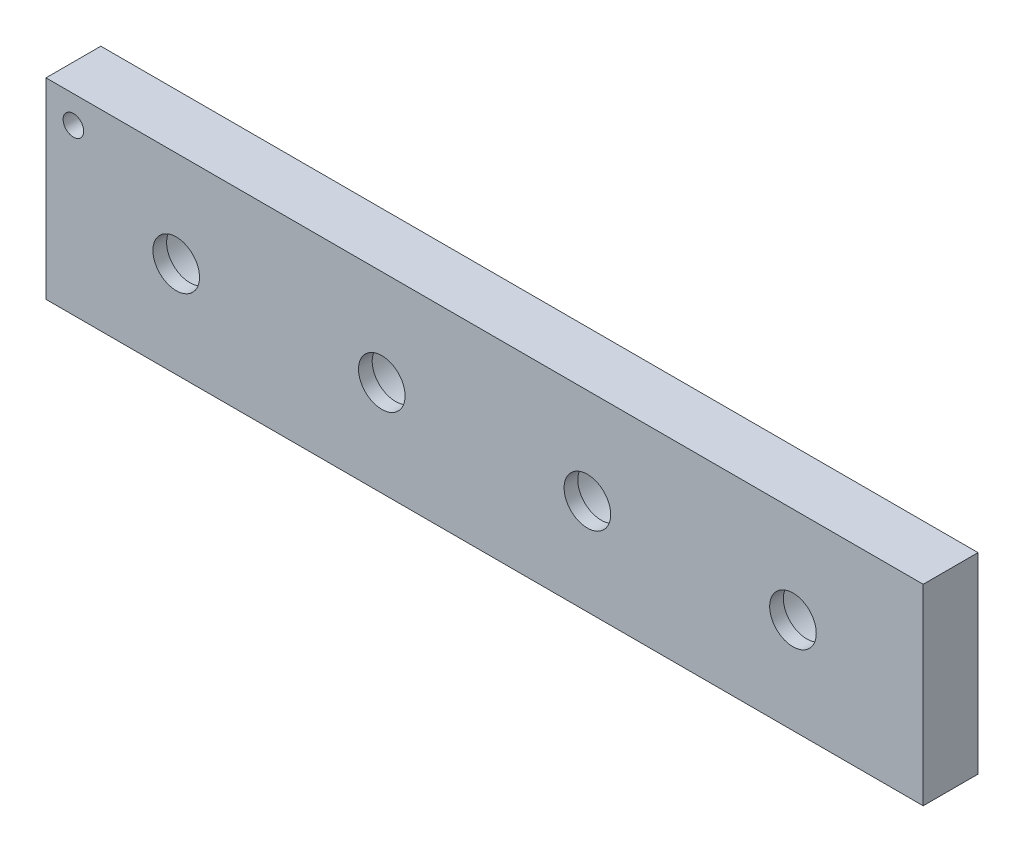
SolidWorks part; units mm, degrees
ref_plane "Front Plane" through (0, 0, 0) normal (0, 0, 1) x (1, 0, 0)
ref_plane "Top Plane" through (0, 0, 0) normal (0, 1, 0) x (1, 0, 0)
ref_plane "Right Plane" through (0, 0, 0) normal (1, 0, 0) x (0, 0, -1)
sketch "Coupon_bar_64x14x4_profile" plane through (0, 0, 0) normal (0, 0, 1) x (1, 0, 0)
  line L1 (-32, -7) -> (32, -7)
  line L2 (-32, -7) -> (-32, 7)
  line L3 (-32, 7) -> (32, 7)
  line L4 (32, -7) -> (32, 7)
  dimension "D1" = 64
  dimension "D2" = 14
extrude "Coupon_bar_64x14x4" add sketch "Coupon_bar_64x14x4_profile" along normal blind 4
sketch "Press_sockets_5p70_5p80_5p90_6p00_depth3_profile" plane through (0, 0, 0) normal (0, 0, 1) x (1, 0, 0)
  circle A0 centre (-22.5, 0) radius 2.85
  circle A1 centre (-7.5, 0) radius 2.9
  circle A2 centre (7.5, 0) radius 2.95
  circle A3 centre (22.5, 0) radius 3
  dimension "D1" = 5.7
  dimension "D2" = 5.8
  dimension "D3" = 5.9
  dimension "D4" = 6
extrude "Press_sockets_5p70_5p80_5p90_6p00_depth3" cut sketch "Press_sockets_5p70_5p80_5p90_6p00_depth3_profile" along normal blind 3
sketch "M3_centre_screw_clearance_profile" plane through (0, 0, 0) normal (0, 0, 1) x (1, 0, 0)
  circle A0 centre (-22.5, 0) radius 1.7
  circle A1 centre (-7.5, 0) radius 1.7
  circle A2 centre (7.5, 0) radius 1.7
  circle A3 centre (22.5, 0) radius 1.7
  dimension "D1" = 3.4
  dimension "D2" = 3.4
  dimension "D3" = 3.4
  dimension "D4" = 3.4
extrude "M3_centre_screw_clearance" cut sketch "M3_centre_screw_clearance_profile" along normal through all from offset 50
sketch "Orientation_mark_at_smallest_socket_profile" plane through (0, 0, 0) normal (0, 0, 1) x (1, 0, 0)
  circle A0 centre (-30, 5) radius 0.75
  dimension "D1" = 1.5
extrude "Orientation_mark_at_smallest_socket" cut sketch "Orientation_mark_at_smallest_socket_profile" along normal through all from offset 50
